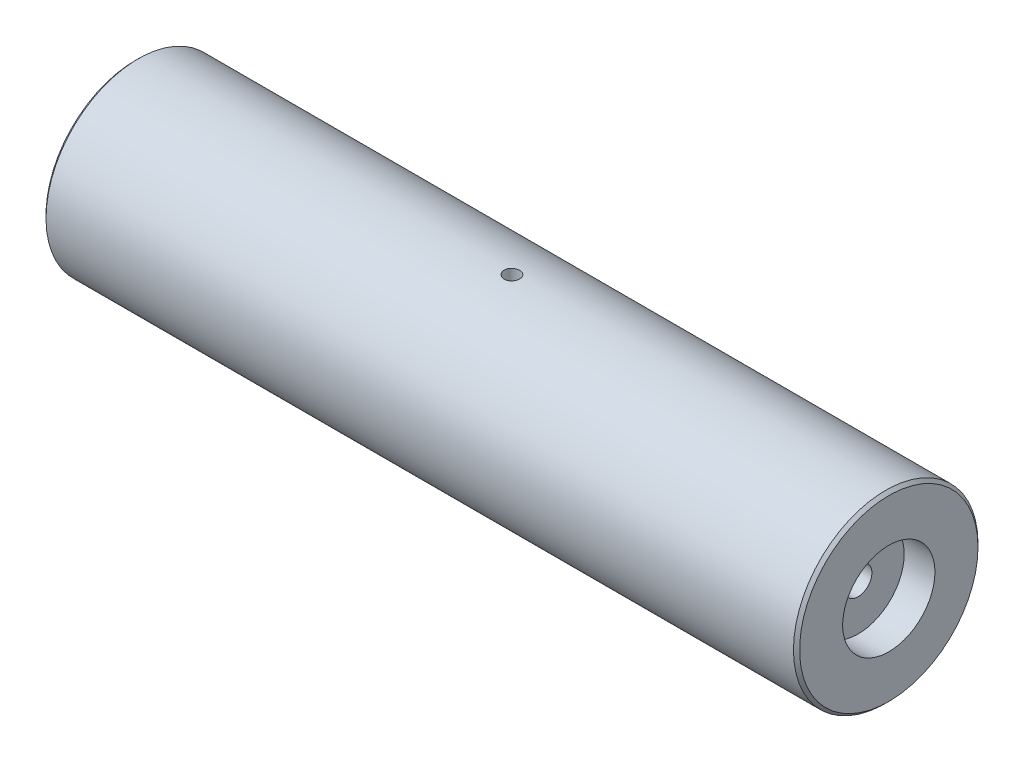
SolidWorks part; units mm, degrees
material "45"
ref_plane "前视基准面" through (0, 0, 0) normal (0, 0, 1) x (1, 0, 0)
ref_plane "上视基准面" through (0, 0, 0) normal (0, 1, 0) x (1, 0, 0)
ref_plane "右视基准面" through (0, 0, 0) normal (1, 0, 0) x (0, 0, -1)
sketch "草图1" plane through (0, 0, 0) normal (1, 0, 0) x (0, 0, -1)
  circle A0 centre (0, 0) radius 30
  dimension "D1" = 60
extrude "凸台-拉伸1" add sketch "草图1" along normal blind 245
chamfer "倒角1" distance 1 angle 45 2 edges at (0, 0, -30) (245, 0, -30)
sketch "草图2" plane through (245, 0, 0) normal (1, 0, 0) x (0, 0, -1)
  circle A0 centre (0, 0) radius 15
  dimension "D1" = 30
extrude "切除-拉伸1" cut sketch "草图2" against normal blind 10
hole_wizard "Ø8.0 (8) 直径孔1" positions "草图3" profile "草图4" hole size "Ø8.0" standard "GB"
sketch "草图3" plane through (235, 0, 0) normal (1, 0, 0) x (0, 0, -1)
  point P0 (0, 0)
sketch "草图4" plane through (235, 0, 0) normal (0, 1, 0) x (0, 0, -1)
  line L0 (0, 0) -> (0, 119.9034)
  line L1 (0, 119.9034) -> (4, 117.5)
  line L2 (4, 117.5) -> (4, 0)
  line L5 (4, 0) -> (0, 0)
  line L10 (0, 119.9034) -> (-4, 117.5) construction
  line L11 (0, -6.35) -> (0, 107.95) construction
  dimension "孔直径" = 8
  dimension "孔深度" = 117.5
  dimension "导头角度" = 118
hole_wizard "M10x1.0 螺纹孔1" positions "草图5" profile "草图6" tap size "M10x1.0" standard "GB"
sketch "草图5" plane through (235, 0, 0) normal (1, 0, 0) x (0, 0, -1)
  point P0 (0, 0)
sketch "草图6" plane through (235, 0, 0) normal (0, 1, 0) x (0, 0, -1)
  line L0 (0, 0) -> (0, 22.7039)
  line L1 (0, 22.7039) -> (4.5, 20)
  line L2 (4.5, 20) -> (4.5, 0)
  line L5 (4.5, 0) -> (0, 0)
  line L10 (0, 22.7039) -> (-4.5, 20) construction
  line L11 (0, -6.35) -> (0, 107.95) construction
  dimension "螺纹孔钻头直径" = 9
  dimension "螺纹孔钻头深度" = 20
  dimension "导头角度" = 118
cosmetic thread "孔螺蚊线1" parameters "D1"=15, "D2"=10
ref_plane "基准面1" through (0, 30, 0) normal (0, 1, 0) x (1, 0, 0)
hole_wizard "Ø5.0 (5) 直径孔1" positions "草图7" profile "草图8" hole size "Ø5.0" standard "GB"
sketch "草图7" plane through (0, 30, 0) normal (0, 1, 0) x (1, 0, 0)
  line L0 (244, 30) -> (1, 30) construction
  line L1 (245, -29) -> (245, 29) construction
  point P0 (122.5, 0)
  dimension "D1" = 30
  dimension "D2" = 122.5
sketch "草图8" plane through (122.5, 30, 0) normal (1, 0, 0) x (0, 0, 1)
  line L0 (0, 0) -> (0, 31.5022)
  line L1 (0, 31.5022) -> (2.5, 30)
  line L2 (2.5, 30) -> (2.5, 0)
  line L5 (2.5, 0) -> (0, 0)
  line L10 (0, 31.5022) -> (-2.5, 30) construction
  line L11 (0, -6.35) -> (0, 107.95) construction
  dimension "孔直径" = 5
  dimension "孔深度" = 30
  dimension "导头角度" = 118
